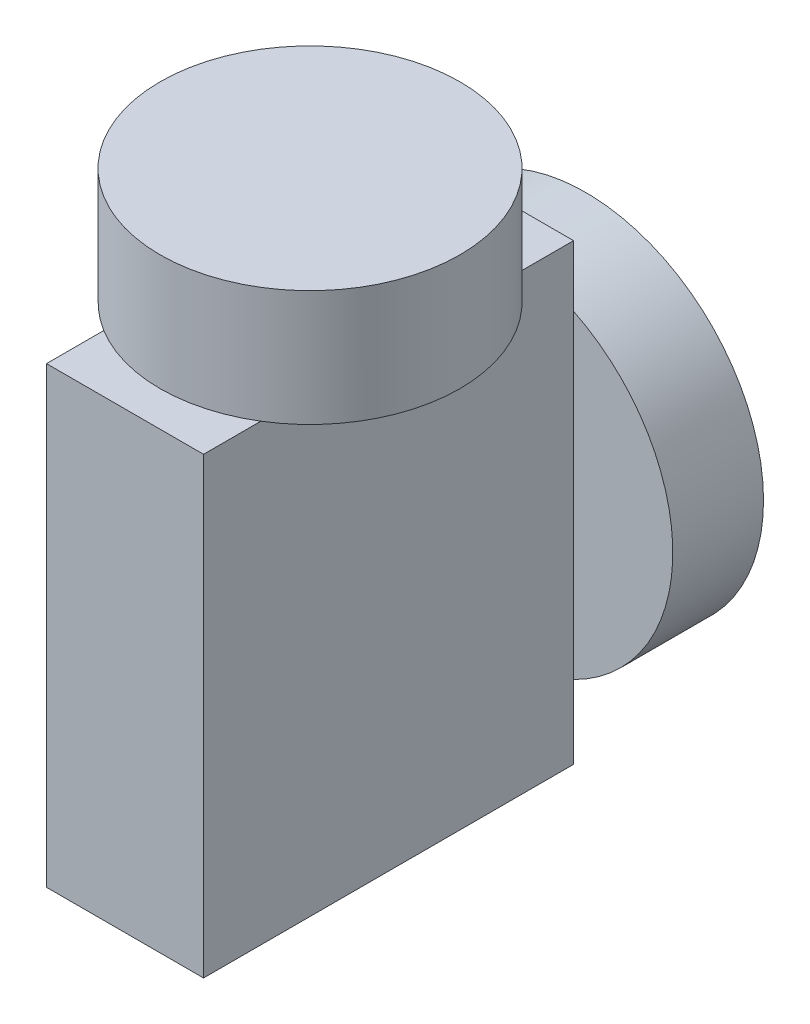
SolidWorks part; units mm, degrees
ref_plane "前视基准面" through (0, 0, 0) normal (0, 0, 1) x (1, 0, 0)
ref_plane "上视基准面" through (0, 0, 0) normal (0, 1, 0) x (1, 0, 0)
ref_plane "右视基准面" through (0, 0, 0) normal (1, 0, 0) x (0, 0, -1)
other "Configuration Table"
sketch "草图1" plane through (0, 0, 0) normal (0, 1, 0) x (1, 0, 0)
  circle A0 centre (0, 0) radius 29.7483
extrude "凸台-拉伸1" add sketch "草图1" along normal blind 23
sketch "草图5" plane through (0, 0, 0) normal (0, -1, 0) x (1, 0, 0)
  line L0 (4.7649, 33.8486) -> (367.6928, -17.2412) construction
  line L1 (15.5828, -36.713) -> (-15.5828, -36.713)
  line L2 (15.5828, -36.713) -> (15.5828, 36.713)
  line L3 (15.5828, 36.713) -> (-15.5828, 36.713)
  line L4 (-15.5828, -36.713) -> (-15.5828, 36.713)
  line L5 (15.5828, -36.713) -> (-15.5828, 36.713) construction
  line L6 (15.5828, 36.713) -> (-15.5828, -36.713) construction
  point P0 (0, 0)
extrude "凸台-拉伸4" add sketch "草图5" along normal blind 90
sketch "草图6" plane through (0, 0, -36.713) normal (0, 0, -1) x (-1, 0, 0)
  circle A0 centre (0, -43.777) radius 35.274
extrude "凸台-拉伸5" add sketch "草图6" along normal blind 18
